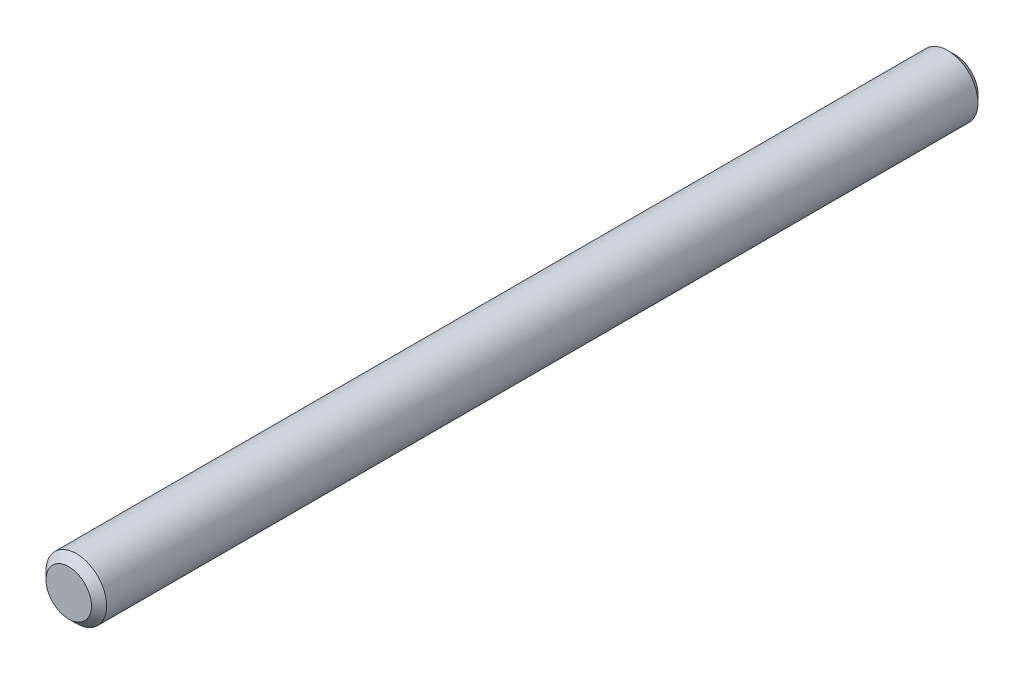
SolidWorks part; units mm, degrees
ref_plane "Front" through (0, 0, 0) normal (0, 0, 1) x (1, 0, 0)
ref_plane "Top" through (0, 0, 0) normal (0, 1, 0) x (1, 0, 0)
ref_plane "Right" through (0, 0, 0) normal (1, 0, 0) x (0, 0, -1)
sketch "Sketch1" plane through (0, 0, 0) normal (0, 0, 1) x (1, 0, 0)
  circle A0 centre (0, 0) radius 0.4
  dimension "D1" = 0.8
extrude "Boss-Extrude1" add sketch "Sketch1" along normal blind 11.7
chamfer "Chamfer1" distance 0.1 angle 45 2 edges at (0.4, 0, 0) (0.4, 0, 11.7)
